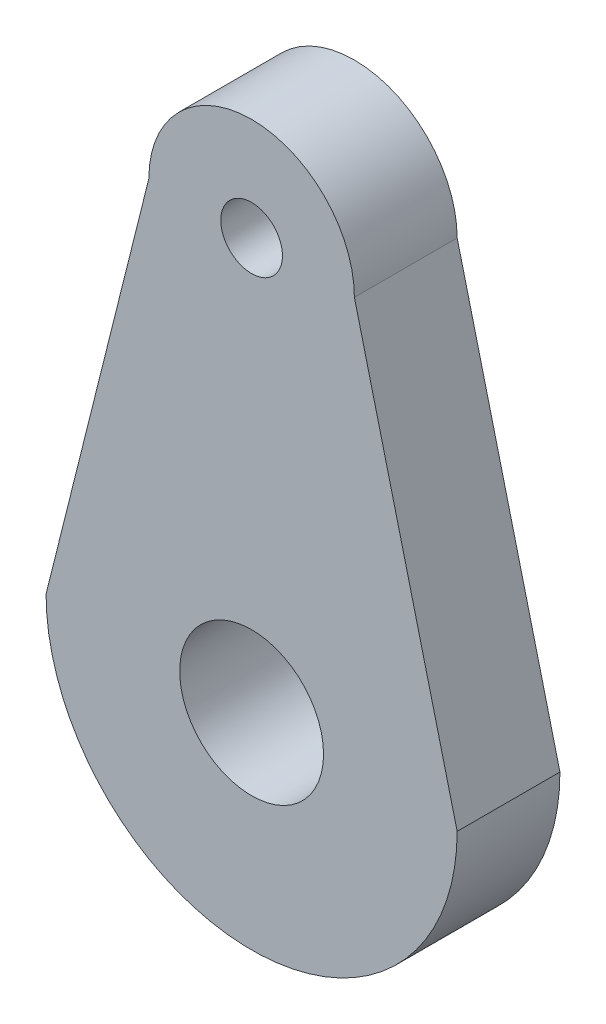
SolidWorks part; units mm, degrees
ref_plane "Front Plane" through (0, 0, 0) normal (0, 0, 1) x (1, 0, 0)
ref_plane "Top Plane" through (0, 0, 0) normal (0, 1, 0) x (1, 0, 0)
ref_plane "Right Plane" through (0, 0, 0) normal (1, 0, 0) x (0, 0, -1)
sketch "Sketch4" plane through (0, 0, 0) normal (0, 0, 1) x (1, 0, 0)
  line L0 (5, 10) -> (10, -10)
  line L1 (-5, 10) -> (-10, -10)
  arc A0 (5, 10) -> (-5, 10) centre (0, 10) ccw
  arc A1 (-10, -10) -> (10, -10) centre (0, -10) ccw
  circle A2 centre (0, -10) radius 3.5
  circle A3 centre (0, 10) radius 1.5
  point P0 (0, 0)
  dimension "D3" = 3
  dimension "D4" = 7
  dimension "D5" = 10
  dimension "D2" = 5
  dimension "D1" = 20
  dimension "D7" = 10
extrude "Boss-Extrude2" add sketch "Sketch4" along normal blind 5
